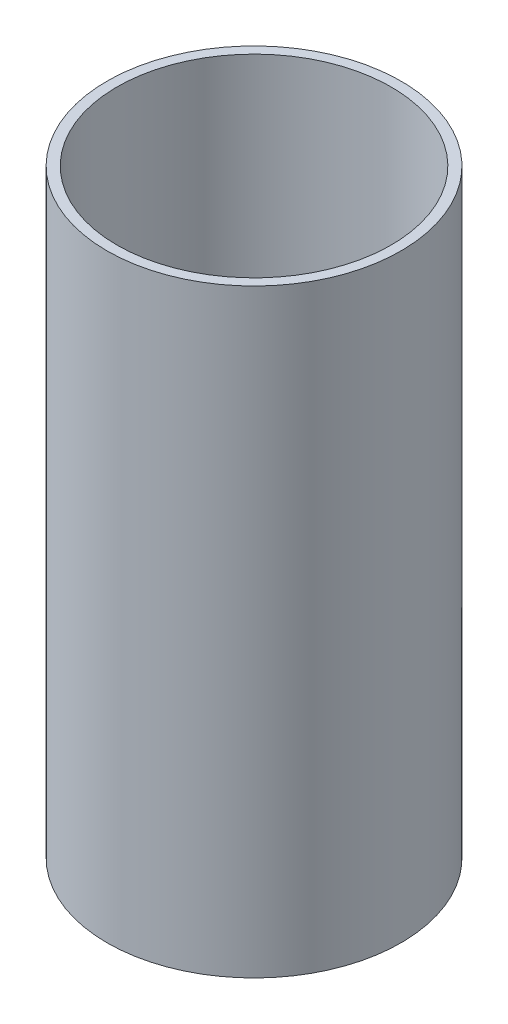
SolidWorks part; units mm, degrees
ref_plane "Plan de face" through (0, 0, 0) normal (0, 0, 1) x (1, 0, 0)
ref_plane "Plan de dessus" through (0, 0, 0) normal (0, 1, 0) x (1, 0, 0)
ref_plane "Plan de droite" through (0, 0, 0) normal (1, 0, 0) x (0, 0, -1)
sketch "Esquisse1" plane through (0, 0, 0) normal (0, 1, 0) x (1, 0, 0)
  circle A0 centre (0, 0) radius 73.61
  circle A1 centre (0, 0) radius 68.61
  dimension "D1" = 147.22
  dimension "D2" = 5
extrude "Boss.-Extru.1" add sketch "Esquisse1" along normal blind 300
ref_plane "Plan1" through (0, 150, 0) normal (0, -1, 0) x (-1, 0, 0)
